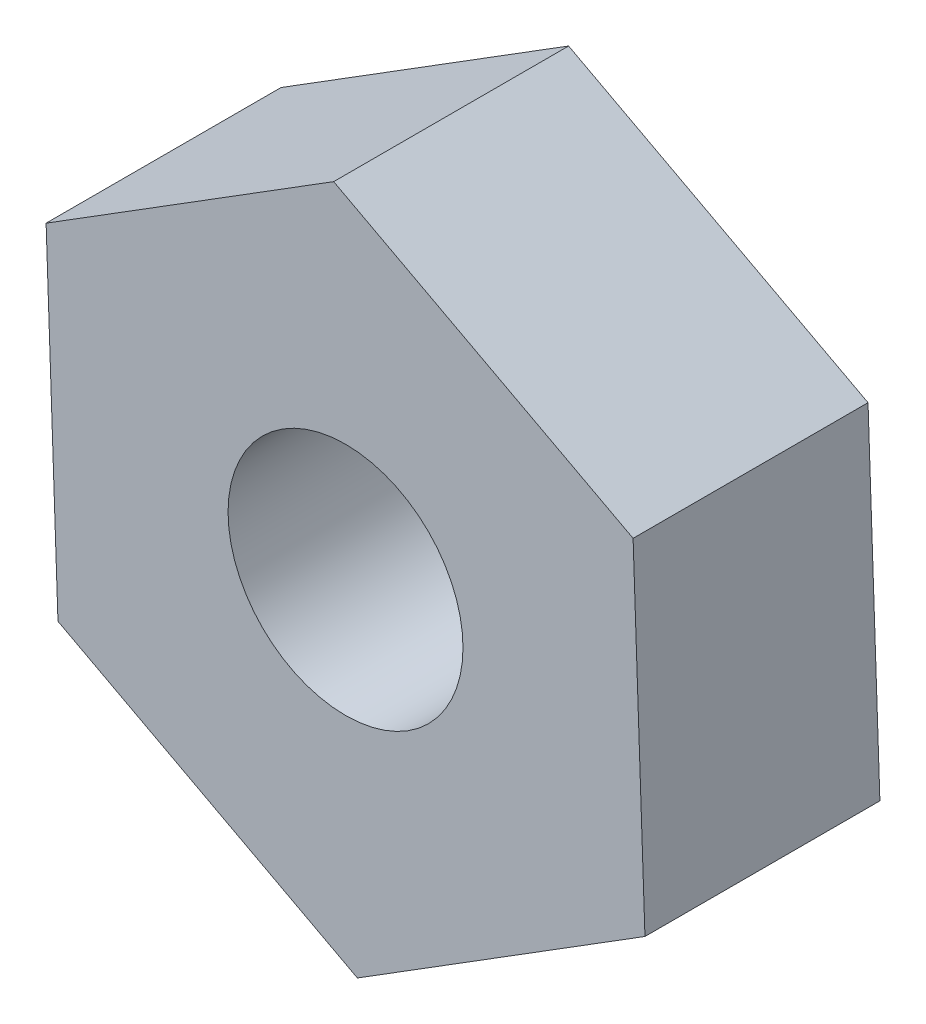
SolidWorks part; units mm, degrees
ref_plane "正面" through (0, 0, 0) normal (0, 0, 1) x (1, 0, 0)
ref_plane "平面" through (0, 0, 0) normal (0, 1, 0) x (1, 0, 0)
ref_plane "右側面" through (0, 0, 0) normal (1, 0, 0) x (0, 0, -1)
sketch "ｽｹｯﾁ1" plane through (0, 0, 0) normal (0, 0, 1) x (1, 0, 0)
  line L1 (2.448, 1.53) -> (-0.101, 2.885)
  line L2 (-0.101, 2.885) -> (-2.549, 1.355)
  line L3 (-2.549, 1.355) -> (-2.448, -1.53)
  line L4 (-2.448, -1.53) -> (0.101, -2.885)
  line L5 (0.101, -2.885) -> (2.549, -1.355)
  line L6 (2.549, -1.355) -> (2.448, 1.53)
  circle A0 centre (0, 0) radius 2.5 construction
  circle A1 centre (0, 0) radius 1
  dimension "D2" = 2
  dimension "D1" = 5
extrude "ﾎﾞｽ - 押し出し1" add sketch "ｽｹｯﾁ1" along normal blind 2
cosmetic thread "ねじ山1"
